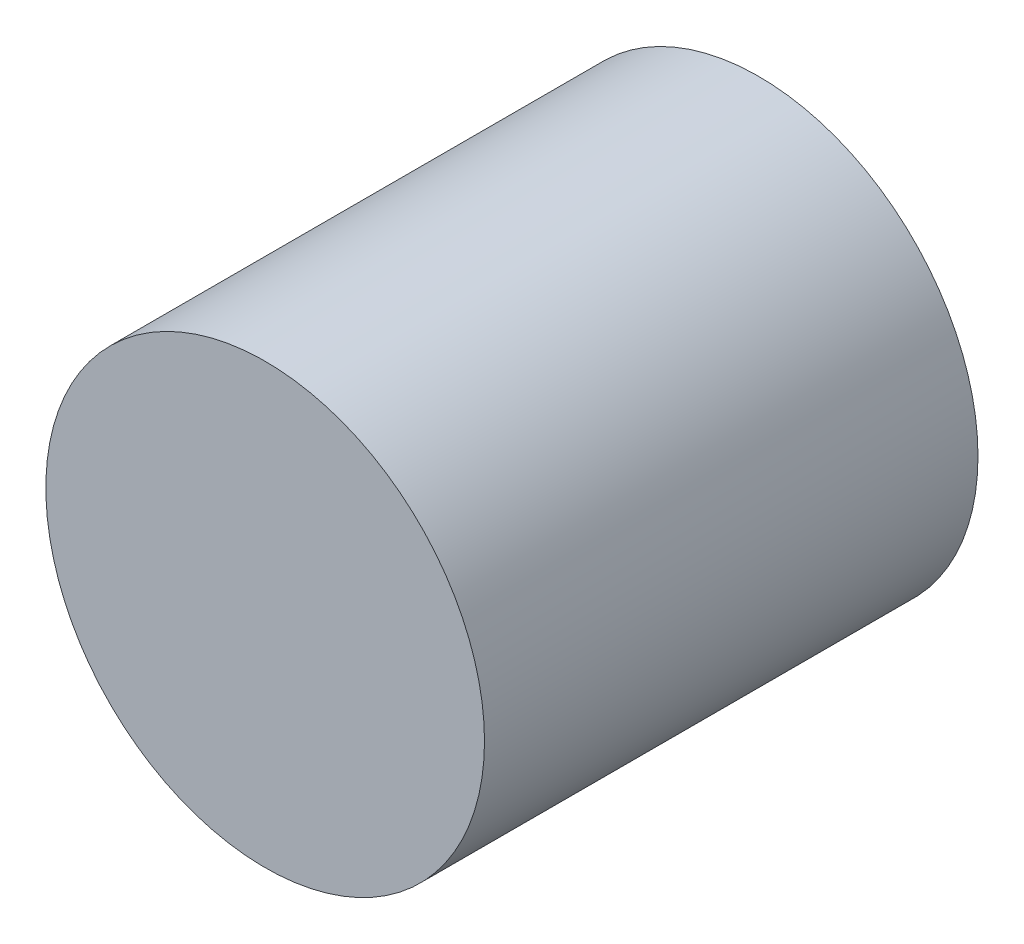
SolidWorks part; units mm, degrees
ref_plane "Front Plane" through (0, 0, 0) normal (0, 0, 1) x (1, 0, 0)
ref_plane "Top Plane" through (0, 0, 0) normal (0, 1, 0) x (1, 0, 0)
ref_plane "Right Plane" through (0, 0, 0) normal (1, 0, 0) x (0, 0, -1)
sketch "Sketch1" plane through (0, 0, 0) normal (0, 0, 1) x (1, 0, 0)
  circle A0 centre (0, 0) radius 2
  dimension "D1" = 4
extrude "Boss-Extrude1" add sketch "Sketch1" along normal blind 4.5
